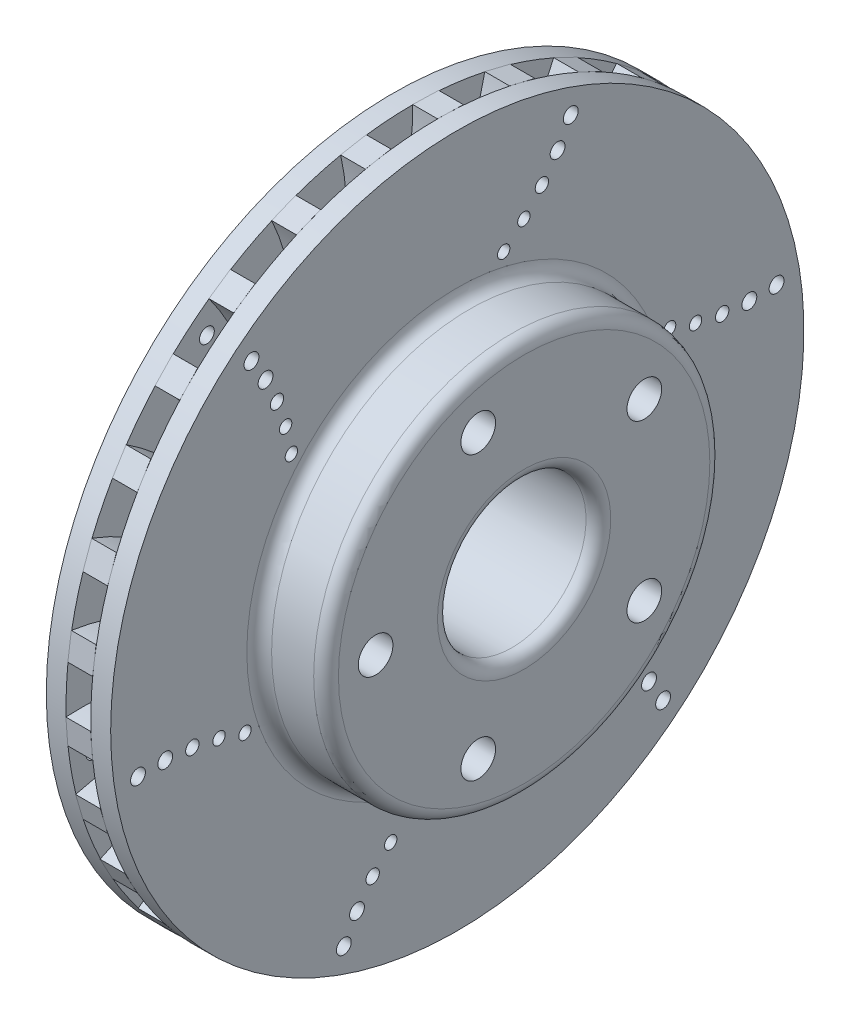
SolidWorks part; units mm, degrees
ref_plane "Front Plane" through (0, 0, 0) normal (0, 0, 1) x (1, 0, 0)
ref_plane "Top Plane" through (0, 0, 0) normal (0, 1, 0) x (1, 0, 0)
ref_plane "Right Plane" through (0, 0, 0) normal (1, 0, 0) x (0, 0, -1)
sketch "Sketch1" plane through (0, 0, 0) normal (0, 0, 1) x (1, 0, 0)
  line L0 (-87.2083, 0) -> (93.1667, 0) construction
  line L1 (13, 140) -> (13, 85)
  line L2 (18, 80) -> (35, 80)
  line L3 (40, 75) -> (40, 35)
  line L4 (35, 30) -> (-35, 30)
  line L5 (-40, 35) -> (-40, 75)
  line L6 (-35, 80) -> (-18, 80)
  line L7 (-13, 85) -> (-13, 140)
  line L8 (-13, 140) -> (-5, 140)
  line L9 (-5, 140) -> (-5, 55)
  line L10 (-10, 50) -> (-25, 50)
  line L11 (-30, 45) -> (-30, 40)
  line L12 (-25, 35) -> (15, 35)
  line L13 (20, 40) -> (20, 50)
  line L14 (15, 55) -> (5, 55)
  line L15 (5, 55) -> (5, 140)
  line L16 (5, 140) -> (13, 140)
  line L17 (0, 0) -> (0, 165.2158) construction
  arc A0 (-25, 50) -> (-30, 45) centre (-25, 45) ccw
  arc A1 (-5, 55) -> (-10, 50) centre (-10, 55) cw
  arc A2 (-18, 80) -> (-13, 85) centre (-18, 85) ccw
  arc A3 (-40, 75) -> (-35, 80) centre (-35, 75) cw
  arc A4 (-35, 30) -> (-40, 35) centre (-35, 35) cw
  arc A5 (40, 35) -> (35, 30) centre (35, 35) cw
  arc A6 (35, 80) -> (40, 75) centre (35, 75) cw
  arc A7 (20, 50) -> (15, 55) centre (15, 50) ccw
  arc A8 (13, 85) -> (18, 80) centre (18, 85) ccw
  arc A9 (15, 35) -> (20, 40) centre (15, 40) ccw
  arc A10 (-30, 40) -> (-25, 35) centre (-25, 40) ccw
  point P22 (0, 30)
  point P28 (-13, 80)
  point P33 (-40, 30)
  point P36 (40, 30)
  point P43 (13, 80)
  dimension "D13" = 5
  dimension "D14" = 5
  dimension "D1" = 26
  dimension "D2" = 140
  dimension "D3" = 80
  dimension "D4" = 5
  dimension "D5" = 8
  dimension "D6" = 30
  dimension "D7" = 20
  dimension "D8" = 80
  dimension "D9" = 13
  dimension "D10" = 15
  dimension "D11" = 20
  dimension "D12" = 30
revolve "Revolve1" add sketch "Sketch1" angle 360 about L0
sketch "Sketch3" plane through (-5, 0, 0) normal (1, 0, 0) x (0, 0, -1)
  line L0 (-0.0008, 140.0622) -> (10.4992, 139.7492)
  line L1 (-13.9534, 78.7737) -> (-21.2682, 77.1211)
  arc A2 (-0.0008, 140.0622) -> (-21.2682, 77.1211) centre (-99.9926, 138.7852) cw
  arc A4 (10.4992, 139.7492) -> (-13.9534, 78.7737) centre (-89.3918, 144.4171) cw
extrude "Boss-Extrude1" add sketch "Sketch3" along normal blind 10
pattern_circular "CirPattern1" count 30 over 360 about axis through (0, 0, 0) along (1, 0, 0) of "Boss-Extrude1"
sketch "Sketch4" plane through (-40, 0, 0) normal (-1, 0, 0) x (0, 0, 1)
  circle A0 centre (0, 0) radius 60 construction
  circle A1 centre (60, 0) radius 7
  circle A2 centre (18.541, -57.0634) radius 7
  circle A3 centre (-48.541, -35.2671) radius 7
  circle A4 centre (-48.541, 35.2671) radius 7
  circle A5 centre (18.541, 57.0634) radius 7
  point P16 (0, 0)
  dimension "D1" = 120
  dimension "D2" = 14
  dimension "D3" = 5
extrude "Cut-Extrude1" cut sketch "Sketch4" against normal up to surface and the other way through all up to face at (40, 0, 75)
sketch "Sketch6" plane through (-13, 0, 0) normal (-1, 0, 0) x (0, 0, 1)
  arc A0 (-49.454, 130.9744) -> (-13.1579, 83.9754) centre (44.2707, 165.8409) ccw construction
  circle A1 centre (0, 0) radius 140 construction
  circle A2 centre (0, 0) radius 85 construction
  circle A4 centre (-45.8249, 122.4499) radius 3
  circle A5 centre (-18.7442, 88.1935) radius 2.5
  circle A6 centre (-26.8913, 95.5844) radius 2.5
  circle A7 centre (-34.1772, 103.8255) radius 2.7
  circle A8 centre (-40.514, 112.8169) radius 3
  circle A9 centre (67.0057, 60.3297) radius 2.5
  circle A10 centre (69.3329, 71.0807) radius 2.5
  circle A11 centre (72.8269, 81.5111) radius 2.7
  circle A12 centre (83.1323, 100.9104) radius 3
  circle A13 centre (77.4453, 91.4946) radius 3
  circle A14 centre (85.7499, -27.8638) radius 2.5
  circle A15 centre (96.2242, -24.5037) radius 2.5
  circle A16 centre (107.0041, -22.3144) radius 2.7
  circle A17 centre (128.9571, -21.5394) radius 3
  circle A18 centre (117.9593, -21.3223) radius 3
  circle A19 centre (18.7442, -88.1935) radius 2.5
  circle A20 centre (26.8913, -95.5844) radius 2.5
  circle A21 centre (34.1772, -103.8255) radius 2.7
  circle A22 centre (45.8249, -122.4499) radius 3
  circle A23 centre (40.514, -112.8169) radius 3
  circle A24 centre (-67.0057, -60.3297) radius 2.5
  circle A25 centre (-69.3329, -71.0807) radius 2.5
  circle A26 centre (-72.8269, -81.5111) radius 2.7
  circle A27 centre (-83.1323, -100.9104) radius 3
  circle A28 centre (-77.4453, -91.4946) radius 3
  circle A29 centre (-85.7499, 27.8638) radius 2.5
  circle A30 centre (-96.2242, 24.5037) radius 2.5
  circle A31 centre (-107.0041, 22.3144) radius 2.7
  circle A32 centre (-128.9571, 21.5394) radius 3
  circle A33 centre (-117.9593, 21.3223) radius 3
  point P70 (0, 0)
  dimension "D1" = 6
  dimension "D3" = 6
  dimension "D4" = 5
  dimension "D5" = 11
  dimension "D8" = 11
  dimension "D2" = 6
  dimension "D6" = 11
  dimension "D7" = 7
  dimension "D9" = 11
extrude "Cut-Extrude4" cut sketch "Sketch6" against normal blind 50
